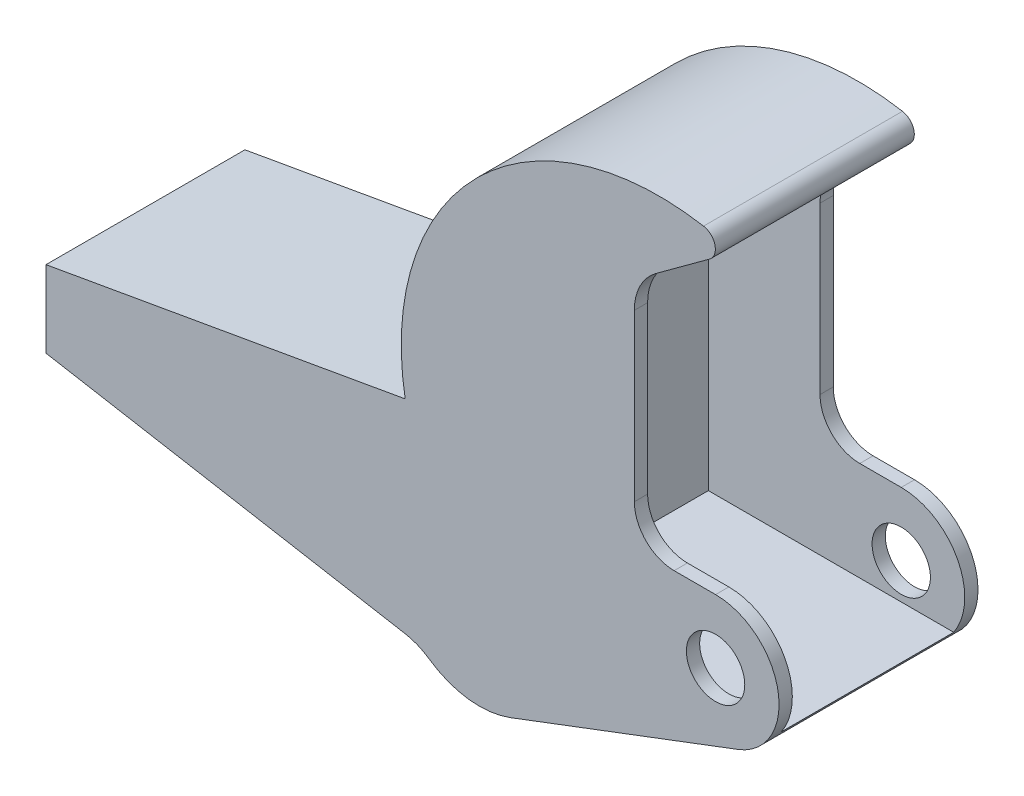
SolidWorks part; units mm, degrees
ref_plane "Front Plane" through (0, 0, 0) normal (0, 0, 1) x (1, 0, 0)
ref_plane "Top Plane" through (0, 0, 0) normal (0, 1, 0) x (1, 0, 0)
ref_plane "Right Plane" through (0, 0, 0) normal (1, 0, 0) x (0, 0, -1)
sketch "Sketch1" plane through (0, 0, 0) normal (0, 0, 1) x (1, 0, 0)
  line L0 (-41.8881, 5.785) -> (12.2763, 15.3356)
  line L6 (12.2763, -15.3356) -> (-41.8881, -5.785)
  line L7 (-41.8881, -5.785) -> (-41.8881, 5.785)
  line L8 (-41.8881, 0) -> (41.8881, 0) construction
  line L10 (58.1771, 56.5429) -> (50.1105, 50.6327)
  line L11 (46.8386, 44.1795) -> (46.8386, 19.1795)
  line L12 (52.8386, 13.1795) -> (59.0886, 13.1795)
  line L15 (28.1731, -18.3526) -> (62.482, -5.3504)
  arc A8 (12.2763, 15.3356) -> (57.2763, 60.3972) centre (50.5755, 22.0888) cw
  arc A10 (50.1105, 50.6327) -> (46.8386, 44.1795) centre (54.8386, 44.1795) ccw
  arc A11 (46.8386, 19.1795) -> (52.8386, 13.1795) centre (52.8386, 19.1795) ccw
  arc A13 (28.1731, -18.3526) -> (15.9158, -16.8375) centre (23.4812, -5.9718) cw
  arc A14 (15.9158, -16.8375) -> (12.2763, -15.3356) centre (10.6874, -24.3466) ccw
  arc A19 (57.2763, 60.3972) -> (58.1771, 56.5429) centre (56.9057, 58.2782) cw
  arc A20 (59.0886, 13.1795) -> (62.482, -5.3504) centre (59.0886, 3.6038) cw
  dimension "D7" = 38.89
  dimension "D9" = 8
  dimension "D11" = 9.15
  dimension "D12" = 13.24
  dimension "D18" = 6
  dimension "D1" = 55
  dimension "D2" = 11.57
  dimension "D3" = 100
  dimension "D4" = 45
  dimension "D5" = 10
  dimension "D8" = 23.3
  dimension "D10" = 25
  dimension "D15" = 6.25
  dimension "D16" = 22.39
extrude "Boss-Extrude1" add sketch "Sketch1" along normal blind 30
sketch "Sketch2" plane through (0, 0, 30) normal (0, 0, 1) x (1, 0, 0)
  circle A0 centre (59.0886, 3.6038) radius 4.4
  arc A1 (62.482, -5.3504) -> (59.0886, 13.1795) centre (59.0886, 3.6038) ccw construction
  point P2 (58.4454, 3.8957)
  dimension "D1" = 8.8
extrude "Cut-Extrude1" cut sketch "Sketch2" against normal through all
ref_plane "Plane1" through (70, 0, 0) normal (1, 0, 0) x (0, 0, -1)
sketch "Sketch4" plane through (70, 0, 0) normal (1, 0, 0) x (0, 0, -1)
  line L1 (-28, 51.4688) -> (-2, 51.4688)
  line L2 (-28, 51.4688) -> (-28, -1.7867)
  line L3 (-28, -1.7867) -> (-2, -1.7867)
  line L4 (-2, 51.4688) -> (-2, -1.7867)
  line L6 (0, 19.1795) -> (0, 44.1795) construction
  line L7 (-30, 19.1795) -> (-30, 44.1795) construction
  point P4 (0, -1.7867)
  point P9 (-30, 56.5429)
  dimension "D1" = 2
  dimension "D2" = 2
extrude "Cut-Extrude2" cut sketch "Sketch4" against normal blind 40
equation "\"A\"= 55mm"
equation "\"D1@Sketch1\"=\"A\""
equation "\"D2@Sketch1\"=\"A\"*(11.57/55)"
equation "\"D7@Sketch1\"=\"A\"*(38.89/55)"
equation "\"D4@Sketch1\"=\"A\"*(45/55)"
equation "\"D5@Sketch1\"=\"A\"*(10/55)"
equation "\"D8@Sketch1\"=\"A\"*(23.3/55)"
equation "\"D9@Sketch1\"=\"A\"*(8/55)"
equation "\"D10@Sketch1\"=\"A\"*(25/55)"
equation "\"D12@Sketch1\"=\"A\"*(13.24/55)"
equation "\"D15@Sketch1\"=\"A\"*(6.25/55)"
equation "\"D18@Sketch1\"=\"A\"*(6/55)"
equation "\"D1@Sketch2\"=\"A\"*(8/50)"
equation "\"D1@Sketch4\"=\"A\"*(2/55)"
equation "\"D2@Sketch4\"=\"A\"*(2/55)"
